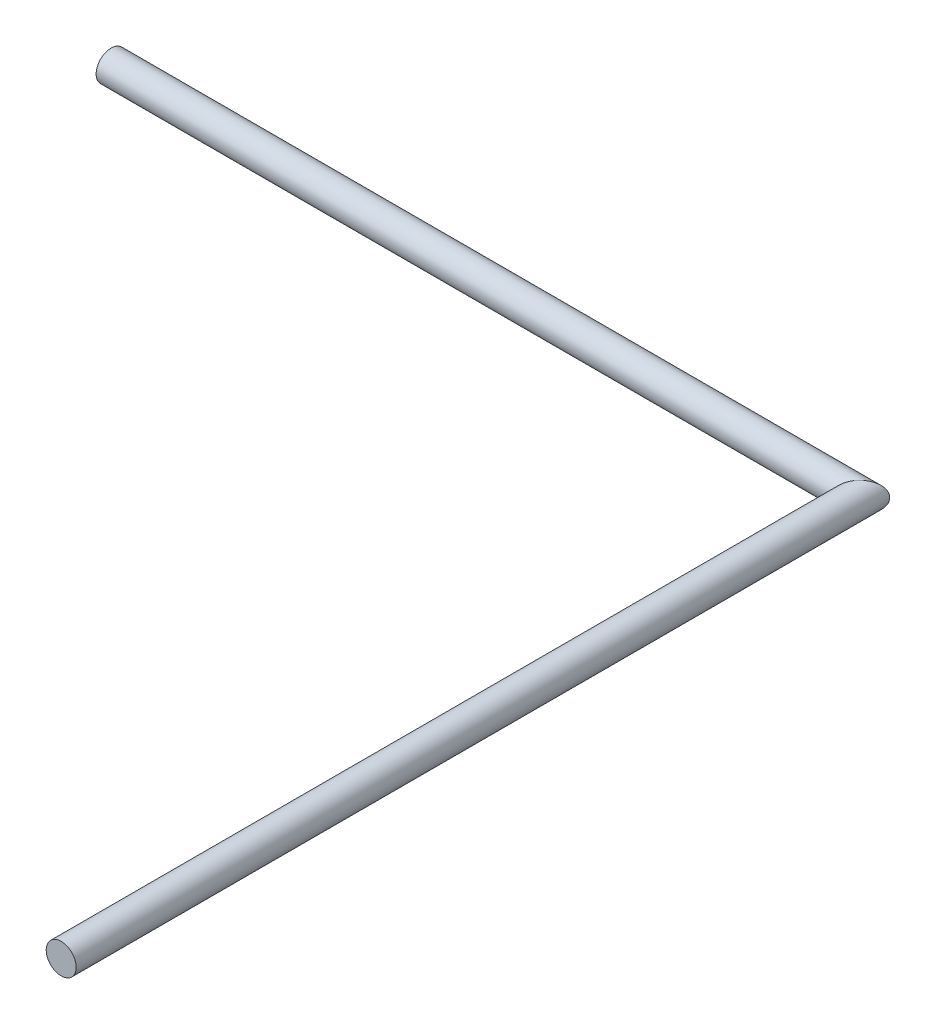
SolidWorks part; units mm, degrees
ref_plane "Front Plane" through (0, 0, 0) normal (0, 0, 1) x (1, 0, 0)
ref_plane "Top Plane" through (0, 0, 0) normal (0, 1, 0) x (1, 0, 0)
ref_plane "Right Plane" through (0, 0, 0) normal (1, 0, 0) x (0, 0, -1)
sketch "Sketch1" plane through (0, 0, 0) normal (0, 1, 0) x (1, 0, 0)
  line L0 (0, 0) -> (150, 0)
  line L1 (150, 0) -> (150, -160)
sketch "Sketch2" plane through (0, 0, 0) normal (1, 0, 0) x (0, 0, -1)
  circle A0 centre (0, 0) radius 3
sweep "Sweep1" add profiles "Sketch2" path "Sketch1"
